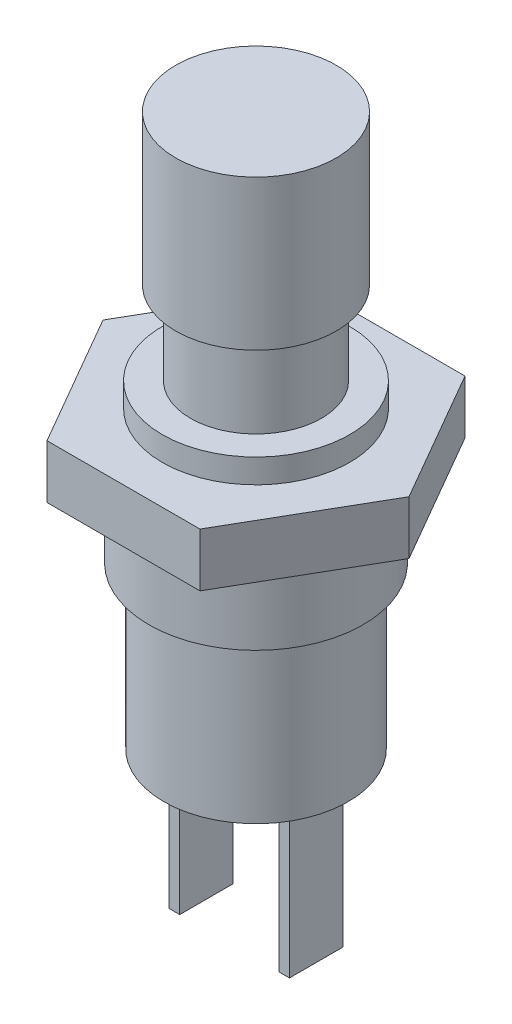
SolidWorks part; units mm, degrees
ref_plane "Front Plane" through (0, 0, 0) normal (0, 0, 1) x (1, 0, 0)
ref_plane "Top Plane" through (0, 0, 0) normal (0, 1, 0) x (1, 0, 0)
ref_plane "Right Plane" through (0, 0, 0) normal (1, 0, 0) x (0, 0, -1)
sketch "Sketch1" plane through (0, 0, 0) normal (0, 0, 1) x (1, 0, 0)
  line L0 (0, 22.727) -> (0, 0) construction
  line L1 (0, 20.6) -> (3, 20.6)
  line L2 (3, 20.6) -> (3, 15)
  line L3 (3, 15) -> (2.4464, 15)
  line L4 (2.4464, 15) -> (2.4464, 11.9)
  line L5 (2.4464, 11.9) -> (3.5, 11.9)
  line L6 (3.5, 11.9) -> (3.5, 11)
  line L7 (3.5, 11) -> (5.715, 11)
  line L8 (5.715, 11) -> (5.715, 9)
  line L9 (5.715, 9) -> (4, 9)
  line L10 (4, 9) -> (4, 6)
  line L11 (4, 6) -> (3.4447, 6)
  line L12 (3.4447, 6) -> (3.4447, 0)
  line L13 (3.4447, 0) -> (0, 0)
  line L14 (0, 20.6) -> (0, 0)
  dimension "D1" = 6
  dimension "D2" = 5.6
  dimension "D3" = 9
  dimension "D4" = 3
  dimension "D5" = 6
  dimension "D6" = 8
  dimension "D7" = 3.1
  dimension "D8" = 2
  dimension "D9" = 7
  dimension "D10" = 11.43
revolve "Revolve2" add sketch "Sketch1" angle 360 about L0
sketch "Sketch2" plane through (0, 11, 0) normal (0, 1, 0) x (1, 0, 0)
  line L1 (5.715, 0) -> (2.8575, 4.9493)
  line L2 (2.8575, 4.9493) -> (-2.8575, 4.9493)
  line L3 (-2.8575, 4.9493) -> (-5.715, 0)
  line L4 (-5.715, 0) -> (-2.8575, -4.9493)
  line L5 (-2.8575, -4.9493) -> (2.8575, -4.9493)
  line L6 (2.8575, -4.9493) -> (5.715, 0)
  circle A0 centre (0, 0) radius 4.9493 construction
  circle A1 centre (0, 0) radius 6.5709
extrude "Cut-Extrude3" cut sketch "Sketch2" against normal blind 5
sketch "Sketch3" plane through (0, 0, 0) normal (0, -1, 0) x (1, 0, 0)
  line L1 (-2.25, -1) -> (-1.85, -1)
  line L2 (-2.25, -1) -> (-2.25, 1)
  line L3 (-2.25, 1) -> (-1.85, 1)
  line L4 (-1.85, -1) -> (-1.85, 1)
  line L5 (-2.25, -1) -> (-1.85, 1) construction
  line L6 (-2.25, 1) -> (-1.85, -1) construction
  line L7 (1.85, -1) -> (2.25, -1)
  line L8 (1.85, -1) -> (1.85, 1)
  line L9 (1.85, 1) -> (2.25, 1)
  line L10 (2.25, -1) -> (2.25, 1)
  line L11 (1.85, -1) -> (2.25, 1) construction
  line L12 (1.85, 1) -> (2.25, -1) construction
  point P0 (-2.05, 0)
  point P5 (2.05, 0)
  point P10 (2.05, 1)
  point P12 (-2.05, 1)
  point P13 (0, 0)
  dimension "D1" = 2
  dimension "D2" = 0.4
  dimension "D3" = 2.05
  dimension "D4" = 2.05
extrude "Boss-Extrude2" add sketch "Sketch3" along normal blind 5.8
